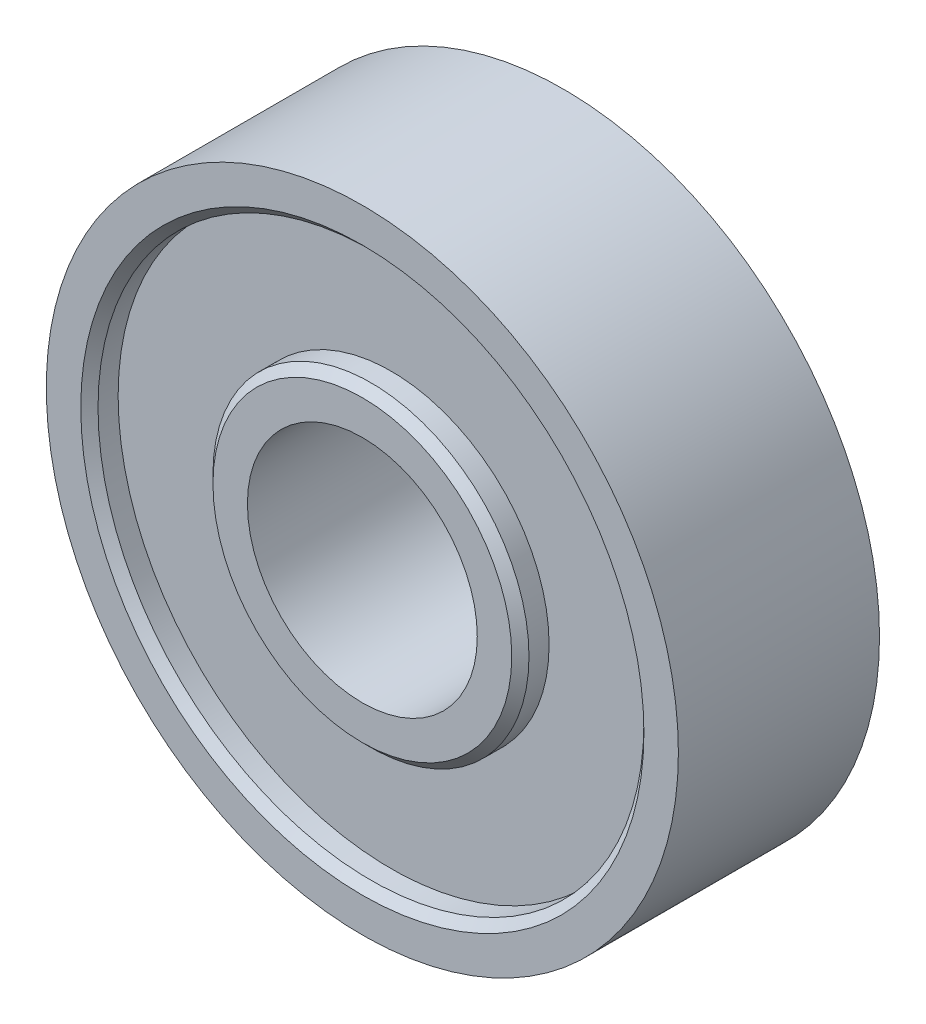
SolidWorks part; units mm, degrees
ref_plane "Alzado" through (0, 0, 0) normal (0, 0, 1) x (1, 0, 0)
ref_plane "Planta" through (0, 0, 0) normal (0, 1, 0) x (1, 0, 0)
ref_plane "Vista lateral" through (0, 0, 0) normal (1, 0, 0) x (0, 0, -1)
sketch "Croquis1" plane through (0, 0, 0) normal (0, 0, 1) x (1, 0, 0)
  circle A0 centre (0, 0) radius 11
  circle A1 centre (0, 0) radius 4
  dimension "D1" = 8
  dimension "D2" = 22
extrude "Saliente-Extruir1" add sketch "Croquis1" along normal mid plane 7
sketch "Croquis2" plane through (0, 0, 3.5) normal (0, 0, 1) x (1, 0, 0)
  circle A0 centre (0, 0) radius 5.5
  circle A1 centre (0, 0) radius 9.5
  circle A2 centre (0, 0) radius 4 construction
  circle A3 centre (0, 0) radius 11 construction
  dimension "D1" = 1.5
  dimension "D2" = 1.5
extrude "Cortar-Extruir1" cut sketch "Croquis2" against normal blind 1
mirror "Simetría1" about plane through (0, 0, 0) normal (0, 0, 1) of "Cortar-Extruir1"
chamfer "Chaflán1" distance 0.3 angle 45 4 edges at (5.5, 0, -3.5) (5.5, 0, 3.5) (9.5, 0, 3.5) (9.5, 0, -3.5)
